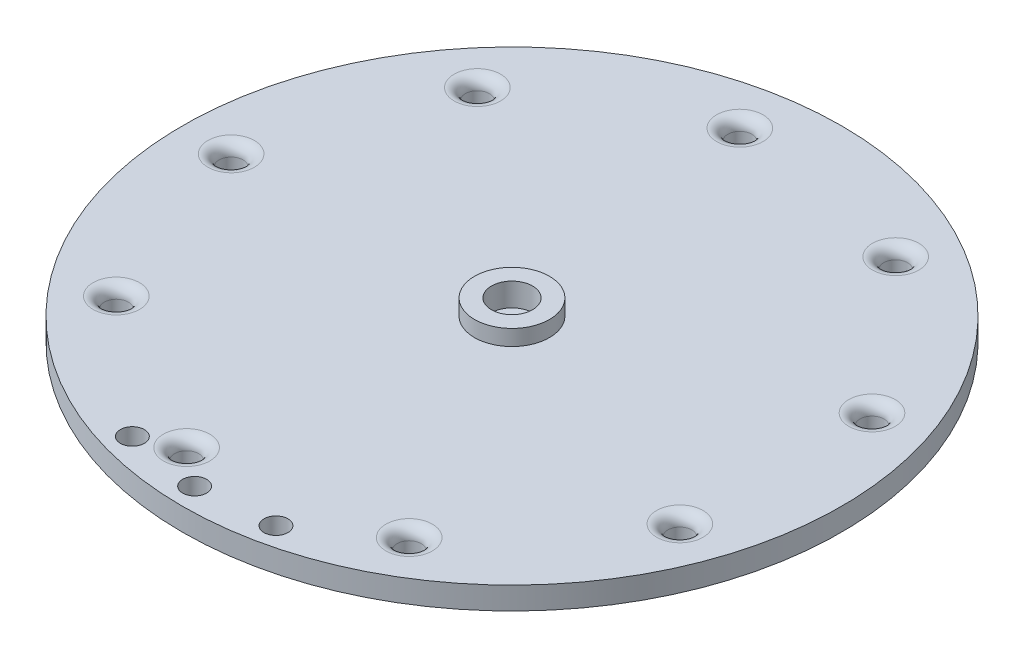
SolidWorks part; units mm, degrees
ref_plane "前视基准面" through (0, 0, 0) normal (0, 0, 1) x (1, 0, 0)
ref_plane "上视基准面" through (0, 0, 0) normal (0, 1, 0) x (1, 0, 0)
ref_plane "右视基准面" through (0, 0, 0) normal (1, 0, 0) x (0, 0, -1)
sketch "草图1" plane through (0, 0, 0) normal (0, 1, 0) x (1, 0, 0)
  line L3 (0, 0) -> (0, 50000) construction
  circle A2 centre (-37.5, 0) radius 1.6
  circle A3 centre (0, 0) radius 37.5 construction
  circle A17 centre (-28.7267, 24.1045) radius 1.6
  circle A18 centre (-6.5118, 36.9303) radius 1.6
  circle A19 centre (18.75, 32.476) radius 1.6
  circle A20 centre (35.2385, 12.8258) radius 1.6
  circle A21 centre (35.2385, -12.8258) radius 1.6
  circle A22 centre (18.75, -32.476) radius 1.6
  circle A23 centre (-6.5118, -36.9303) radius 1.6
  circle A24 centre (-28.7267, -24.1045) radius 1.6
  circle A28 centre (0, 0) radius 44
  circle A29 centre (0, 0) radius 2
  point P27 (0, 0)
  point P45 (0, 0)
  dimension "D1" = 88
  dimension "D4" = 3.2
  dimension "D5" = 75
  dimension "D2" = 4
  dimension "D6" = 9
extrude "凸台-拉伸1" add sketch "草图1" along normal mid plane 3
sketch "草图2" plane through (0, 1.5, 0) normal (0, 1, 0) x (1, 0, 0)
  line L0 (0, 44) -> (0, -44) construction
  line L1 (44, 0) -> (-44, 0) construction
  line L2 (2.5, 34.9106) -> (2.5, 24.8747)
  line L3 (24.8747, 2.5) -> (34.9212, 2.5)
  line L4 (19.8431, 2.5) -> (7.5993, 2.5)
  line L5 (2.5, 19.8431) -> (2.5, 7.5993)
  line L6 (2.5, -24.8747) -> (2.5, -34.9212)
  line L7 (34.9106, -2.5) -> (24.8747, -2.5)
  line L8 (19.8431, -2.5) -> (7.5993, -2.5)
  line L9 (2.5, -19.8431) -> (2.5, -7.5993)
  line L10 (-24.8747, -2.5) -> (-34.9212, -2.5)
  line L11 (-2.5, -34.9106) -> (-2.5, -24.8747)
  line L12 (-2.5, -19.8431) -> (-2.5, -7.5993)
  line L13 (-19.8431, -2.5) -> (-7.5993, -2.5)
  line L14 (-2.5, 24.8747) -> (-2.5, 34.9212)
  line L15 (-34.9106, 2.5) -> (-24.8747, 2.5)
  line L16 (-19.8431, 2.5) -> (-7.5993, 2.5)
  line L17 (-2.5, 19.8431) -> (-2.5, 7.5993)
  circle A0 centre (0, 0) radius 44 construction
  arc A1 (2.5, 34.9106) -> (34.9106, 2.5) centre (0, 0) cw
  arc A2 (24.8747, 2.5) -> (2.5, 24.8747) centre (0, 0) ccw
  arc A3 (19.8431, 2.5) -> (2.5, 19.8431) centre (0, 0) ccw
  arc A4 (2.5, -24.8747) -> (24.8747, -2.5) centre (0, 0) ccw
  arc A5 (34.9106, -2.5) -> (2.5, -34.9106) centre (0, 0) cw
  arc A6 (7.5993, 2.5) -> (2.5, 7.5993) centre (0, 0) ccw
  arc A7 (2.5, -7.5993) -> (7.5993, -2.5) centre (0, 0) ccw
  arc A8 (2.5, -19.8431) -> (19.8431, -2.5) centre (0, 0) ccw
  arc A9 (-24.8747, -2.5) -> (-2.5, -24.8747) centre (0, 0) ccw
  arc A10 (-2.5, -34.9106) -> (-34.9106, -2.5) centre (0, 0) cw
  arc A11 (-7.5993, -2.5) -> (-2.5, -7.5993) centre (0, 0) ccw
  arc A12 (-19.8431, -2.5) -> (-2.5, -19.8431) centre (0, 0) ccw
  arc A13 (-2.5, 24.8747) -> (-24.8747, 2.5) centre (0, 0) ccw
  arc A14 (-34.9106, 2.5) -> (-2.5, 34.9106) centre (0, 0) cw
  arc A15 (-2.5, 7.5993) -> (-7.5993, 2.5) centre (0, 0) ccw
  arc A16 (-2.5, 19.8431) -> (-19.8431, 2.5) centre (0, 0) ccw
  point P47 (0, 0)
  dimension "D1" = 2.5
  dimension "D3" = 35
  dimension "D4" = 25
  dimension "D5" = 20
  dimension "D6" = 8
  dimension "D2" = 2.5
  dimension "D7" = 4
sketch "草图3" plane through (0, -1.5, 0) normal (0, -1, 0) x (1, 0, 0)
  circle A0 centre (8.4882, 40) radius 1.6
  circle A1 centre (-6.5118, 36.9303) radius 1.6 construction
  circle A2 centre (-1.5118, 40.8627) radius 1.6
  circle A3 centre (-11.4207, 39.2634) radius 1.6
  point P12 (0, 0)
  dimension "D1" = 40
  dimension "D2" = 3.2
  dimension "D3" = 15
  dimension "D5" = 10
  dimension "D4" = 3
extrude "切除-拉伸4" cut sketch "草图3" against normal blind 10
sketch "草图4" plane through (0, 1.5, 0) normal (0, 1, 0) x (1, 0, 0)
  circle A0 centre (0, 0) radius 2.4
  dimension "D1" = 4.8
extrude "凸台-拉伸2" add sketch "草图4" along normal blind 10 and the other way blind 3 contours A0
sketch "草图5" plane through (0, 11.5, 0) normal (0, 1, 0) x (1, 0, 0)
  circle A0 centre (0, 0) radius 1.6
  dimension "D1" = 3.2
extrude "切除-拉伸5" cut sketch "草图5" against normal through all
sketch "草图6" plane through (0, 1.5, 0) normal (0, 1, 0) x (1, 0, 0)
  circle A0 centre (0, 0) radius 5
  circle A1 centre (0, 0) radius 1.6
  dimension "D1" = 10
  dimension "D2" = 3.2
extrude "凸台-拉伸3" add sketch "草图6" along normal blind 2.1
fillet "圆角1" radius 1.5 9 edges at (35.2385, 1.5, -11.2258) (-6.5118, 1.5, 38.5303) (18.75, 1.5, 34.076) (35.2385, 1.5, 14.4258) (18.75, 1.5, -30.876) (-6.5118, 1.5, -35.3303) (-28.7267, 1.5, -22.5045) (-37.5, 1.5, 1.6) (-28.7267, 1.5, 25.7045)
sketch "草图7" plane through (0, 11.5, 0) normal (0, 1, 0) x (1, 0, 0)
  circle A0 centre (0, 0) radius 2.75
  dimension "D1" = 5.5
extrude "切除-拉伸6" cut sketch "草图7" against normal blind 11
